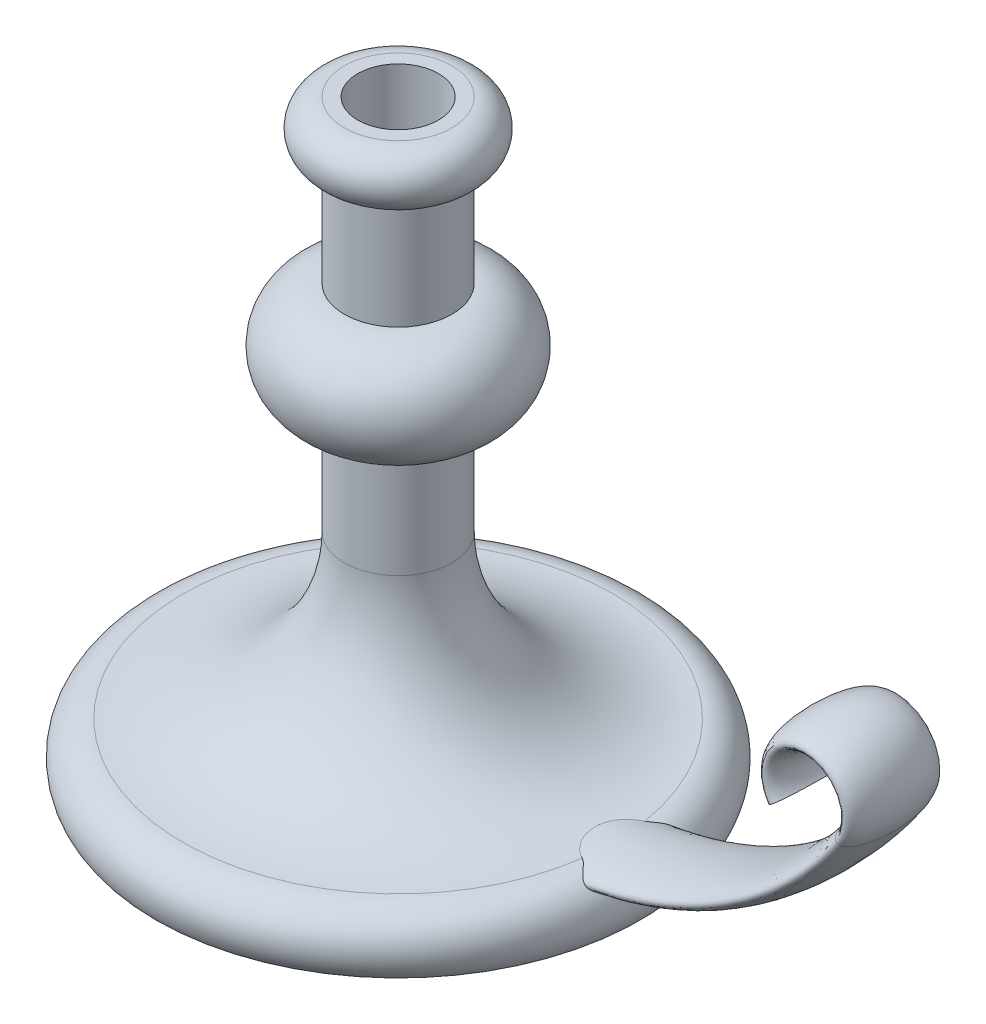
SolidWorks part; units mm, degrees
ref_plane "Alzado" through (0, 0, 0) normal (0, 0, 1) x (1, 0, 0)
ref_plane "Planta" through (0, 0, 0) normal (0, 1, 0) x (1, 0, 0)
ref_plane "Vista lateral" through (0, 0, 0) normal (1, 0, 0) x (0, 0, -1)
sketch "Croquis1" plane through (0, 0, 0) normal (0, 0, 1) x (1, 0, 0)
  line L0 (0, 0) -> (0, 220)
  line L1 (0, 220) -> (20, 220)
  line L2 (0, 0) -> (90, 0)
  line L3 (20, 200) -> (20, 160)
  line L4 (20, 120) -> (20, 80)
  arc A0 (20, 220) -> (20, 200) centre (20, 210) cw
  arc A1 (20, 160) -> (20, 120) centre (20, 140) cw
  arc A2 (20, 80) -> (80, 20) centre (80, 80) ccw
  arc A3 (80, 20) -> (90, 0) centre (80, 7.5) cw
  point P7 (30, 210)
  dimension "D3" = 10
  dimension "D4" = 20
  dimension "D7" = 60
  dimension "D8" = 12.5
  dimension "D1" = 220
  dimension "D2" = 20
  dimension "90" = 90
  dimension "D5" = 40
  dimension "D6" = 40
  dimension "D9" = 80
revolve "Revolución1" add sketch "Croquis1" angle 360 about L0
sketch "Croquis2" plane through (0, 0, 0) normal (0, 0, 1) x (1, 0, 0)
  line L0 (0, 10) -> (60, 10)
  line L1 (0, 227.4356) -> (0, 175.1288) construction
  line L2 (0, 200) -> (0, 160) construction
  line L3 (-90, 0) -> (90, 0) construction
  arc A0 (60, 10) -> (183.5921, 75) centre (60, 160) ccw
  arc A1 (183.5921, 75) -> (150.6342, 75) centre (167.1131, 86.3333) ccw
  point P10 (0, 0)
  point P11 (0, 0)
  point P12 (0, 0)
  point P13 (0, 0)
  point P16 (0, 0)
  point P17 (0, 0)
  point P18 (0, 0)
  dimension "D2" = 150
  dimension "D4" = 20
  dimension "D1" = 60
  dimension "D3" = 65
  dimension "D5" = 10
sketch "Croquis4" plane through (0, 0, 0) normal (1, 0, 0) x (0, 0, -1)
  ellipse E0 centre (1.0155, 15) end of major axis (18.5155, 15) minor radius 5
  point P1 (0, 0)
  point P7 (0, 0)
  point P8 (0, 0)
  dimension "D1" = 10
  dimension "D2" = 35
  dimension "D3" = 0
sweep "Barrer1" add profiles "Croquis4" path "Croquis2"
sketch "Croquis5" plane through (0, 220, 0) normal (0, 1, 0) x (1, 0, 0)
  circle A0 centre (0, 0) radius 15
  dimension "D1" = 30
extrude "Cortar-Extruir1" cut sketch "Croquis5" against normal blind 25
